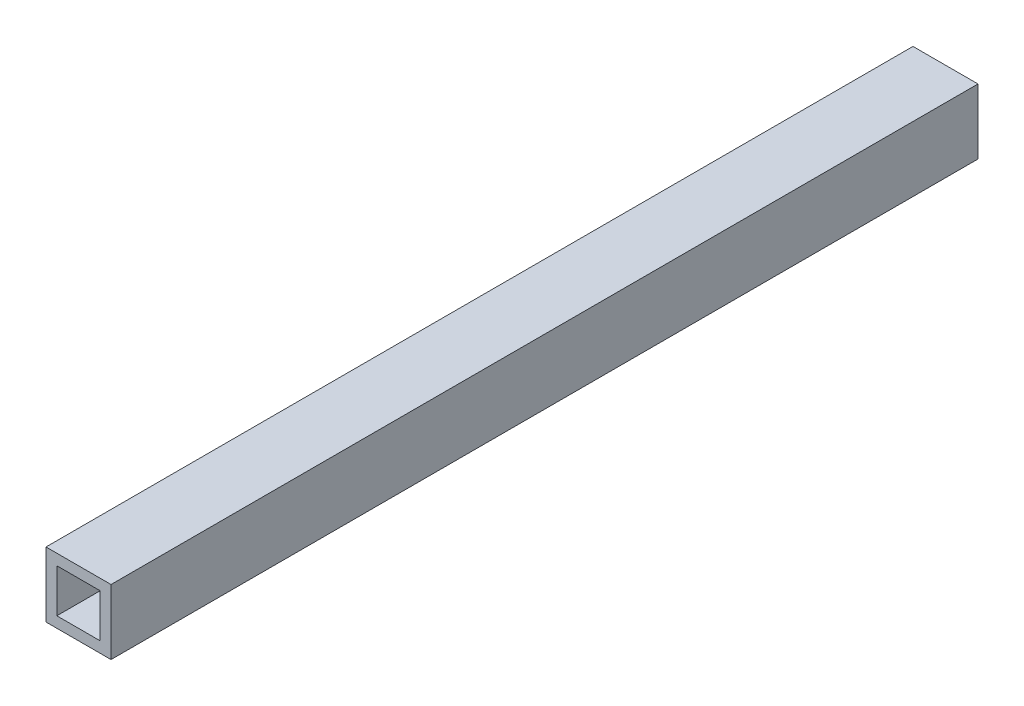
SolidWorks part; units mm, degrees
material "AISI 1010 Steel, hot rolled bar"
ref_plane "Front Plane" through (0, 0, 0) normal (0, 0, 1) x (1, 0, 0)
ref_plane "Top Plane" through (0, 0, 0) normal (0, 1, 0) x (1, 0, 0)
ref_plane "Right Plane" through (0, 0, 0) normal (1, 0, 0) x (0, 0, -1)
sketch "Sketch1" plane through (0, 0, 0) normal (0, 0, 1) x (1, 0, 0)
  line L1 (-15, 15) -> (15, 15)
  line L2 (-15, 15) -> (-15, -15)
  line L3 (-15, -15) -> (15, -15)
  line L4 (15, 15) -> (15, -15)
  line L5 (-15, 15) -> (15, -15) construction
  line L6 (-15, -15) -> (15, 15) construction
  line L7 (-10, 10) -> (10, 10)
  line L8 (-10, 10) -> (-10, -10)
  line L9 (-10, -10) -> (10, -10)
  line L10 (10, 10) -> (10, -10)
  line L11 (-10, 10) -> (10, -10) construction
  line L12 (-10, -10) -> (10, 10) construction
  point P0 (0, 0)
  point P6 (0, 0)
  dimension "D1" = 30
  dimension "D2" = 30
  dimension "D3" = 5
extrude "Boss-Extrude1" add sketch "Sketch1" along normal blind 400
equation "\"3.00d\"=3"
